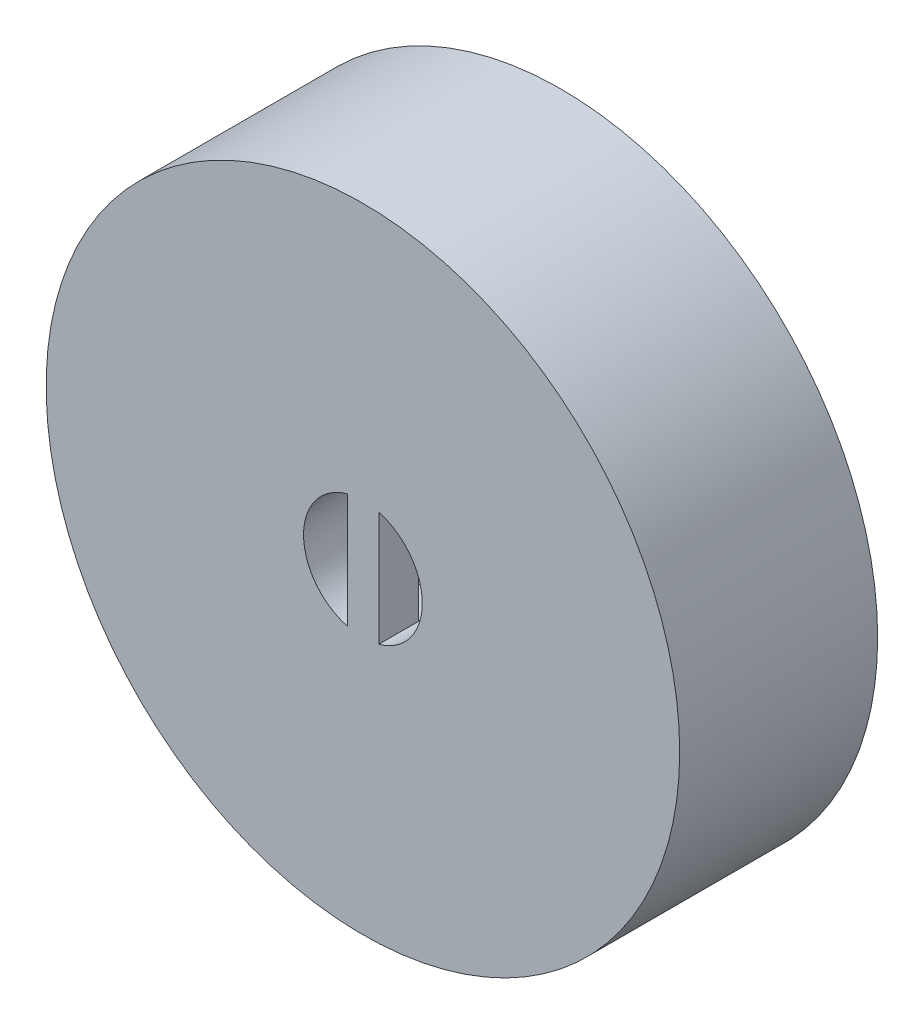
SolidWorks part; units mm, degrees
material "Plain Carbon Steel"
ref_plane "Front Plane" through (0, 0, 0) normal (0, 0, 1) x (1, 0, 0)
ref_plane "Top Plane" through (0, 0, 0) normal (0, 1, 0) x (1, 0, 0)
ref_plane "Right Plane" through (0, 0, 0) normal (1, 0, 0) x (0, 0, -1)
sketch "Sketch1" plane through (0, 0, 0) normal (0, 0, 1) x (1, 0, 0)
  circle A0 centre (-6.5756, 0) radius 25.4
  dimension "D1" = 50.8
extrude "Boss-Extrude1" add sketch "Sketch1" along normal blind 15.875
sketch "Sketch2" plane through (0, 0, 15.875) normal (0, 0, 1) x (1, 0, 0)
  line L3 (-7.8242, 4.5959) -> (-7.8242, -4.5959)
  line L4 (-5.3056, 4.59) -> (-5.3056, -4.59)
  arc A0 (-7.8242, 4.5959) -> (-7.8242, -4.5959) centre (-6.5756, 0) ccw
  arc A1 (-5.3056, -4.59) -> (-5.3056, 4.59) centre (-6.5756, 0) ccw
  dimension "D1" = 9.525
sketch "Sketch6" plane through (0, 0, 0) normal (0, 0, -1) x (-1, 0, 0)
  circle A0 centre (6.5756, 0) radius 9.525
  dimension "D1" = 19.05
extrude "Boss-Extrude3" add sketch "Sketch6" along normal blind 9.525
extrude "Cut-Extrude3" cut sketch "Sketch2" against normal through all both and the other way through all contours L3 A0 | A1 L4
sketch "Sketch10" plane through (0, 0, -9.525) normal (0, 0, -1) x (-1, 0, 0)
  line L0 (5.3056, 4.59) -> (5.3056, -4.59)
  line L1 (7.8242, 4.5959) -> (7.8242, -4.5959)
  line L2 (5.3056, -4.59) -> (7.8242, -4.5959)
  line L3 (5.3056, 4.59) -> (7.8242, 4.5959)
sketch "Sketch11" plane through (0, 0, 0) normal (0, 1, 0) x (1, 0, 0)
  line L0 (-6.5649, 9.525) -> (-6.5756, -15.875) construction
  line L1 (-5.3056, 9.525) -> (-7.8242, 9.525) construction
  line L2 (-31.9756, -15.875) -> (18.8244, -15.875) construction
extrude "Cut-Extrude5" cut sketch "Sketch10" against normal blind 22.225 contours L2 L1 L3 L0
